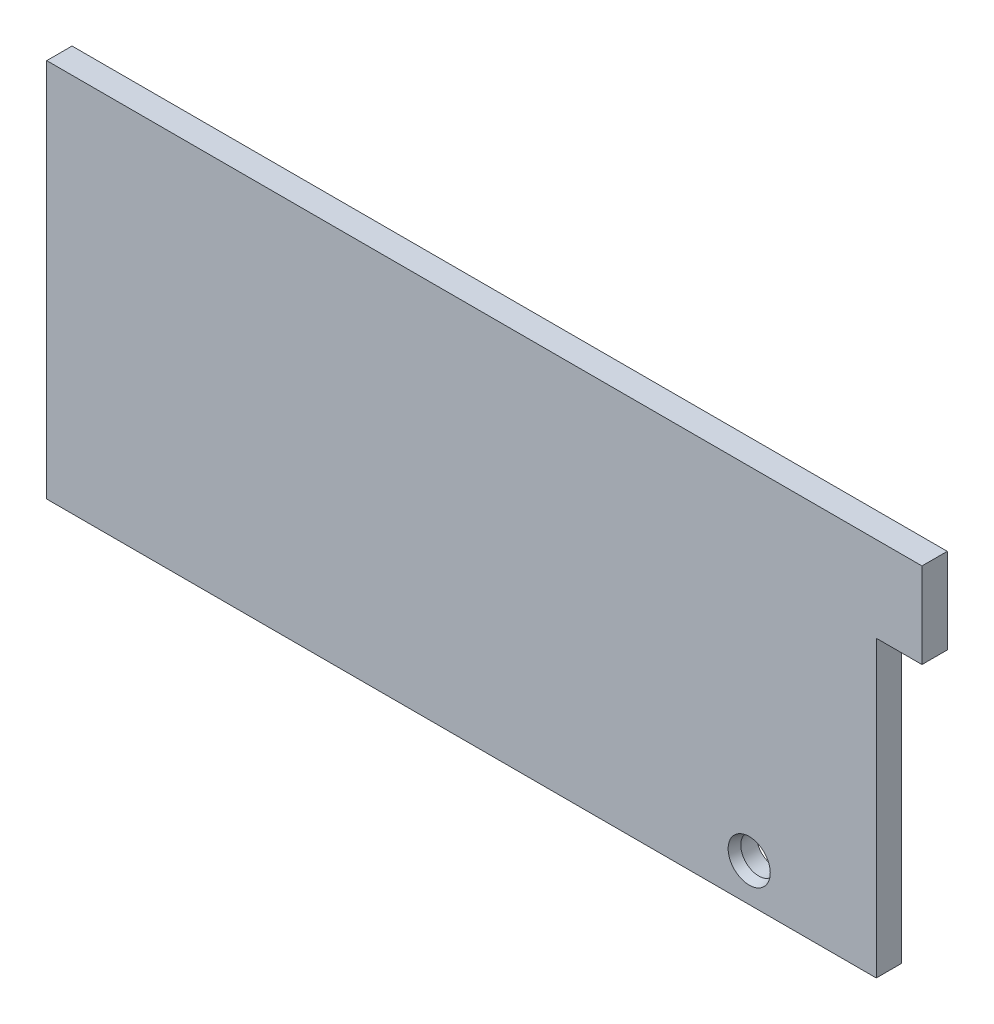
SolidWorks part; units mm, degrees
ref_plane "Front Plane" through (0, 0, 0) normal (0, 0, 1) x (1, 0, 0)
ref_plane "Top Plane" through (0, 0, 0) normal (0, 1, 0) x (1, 0, 0)
ref_plane "Right Plane" through (0, 0, 0) normal (1, 0, 0) x (0, 0, -1)
sketch "Sketch1" plane through (0, 0, 0) normal (0, 0, 1) x (1, 0, 0)
  line L1 (-81, -30) -> (50.0797, -30)
  line L6 (57.3, 16.5) -> (50.0797, 16.5)
  line L11 (57.3, 16.5) -> (57.3, 30)
  line L13 (50.0797, 16.5) -> (50.0797, -30)
  line L18 (57.3, 30) -> (-81, 30)
  line L19 (-81, 30) -> (-81, -30)
  circle A4 centre (-41, 0) radius 5 construction
  circle A5 centre (30, -24) radius 2.83
  point P4 (-81, 0)
  dimension "D5" = 10
  dimension "D9" = 5.66
  dimension "D8" = 13.5
  dimension "D10" = 60
  dimension "D2" = 138.3
  dimension "D3" = 40
  dimension "D4" = 71
  dimension "D6" = 24
extrude "Boss-Extrude1" add sketch "Sketch1" along normal mid plane 4
chamfer "Chamfer1" distance 0.5 distance2 1.5 1 edges at (32.83, -24, 2)
equation "\"back_boost\"= 7"
equation "\"D3@Sketch1\"=\"back_boost\"+33.00mm"
equation "\"D2@Sketch1\"=\"back_boost\"+131.30mm"
